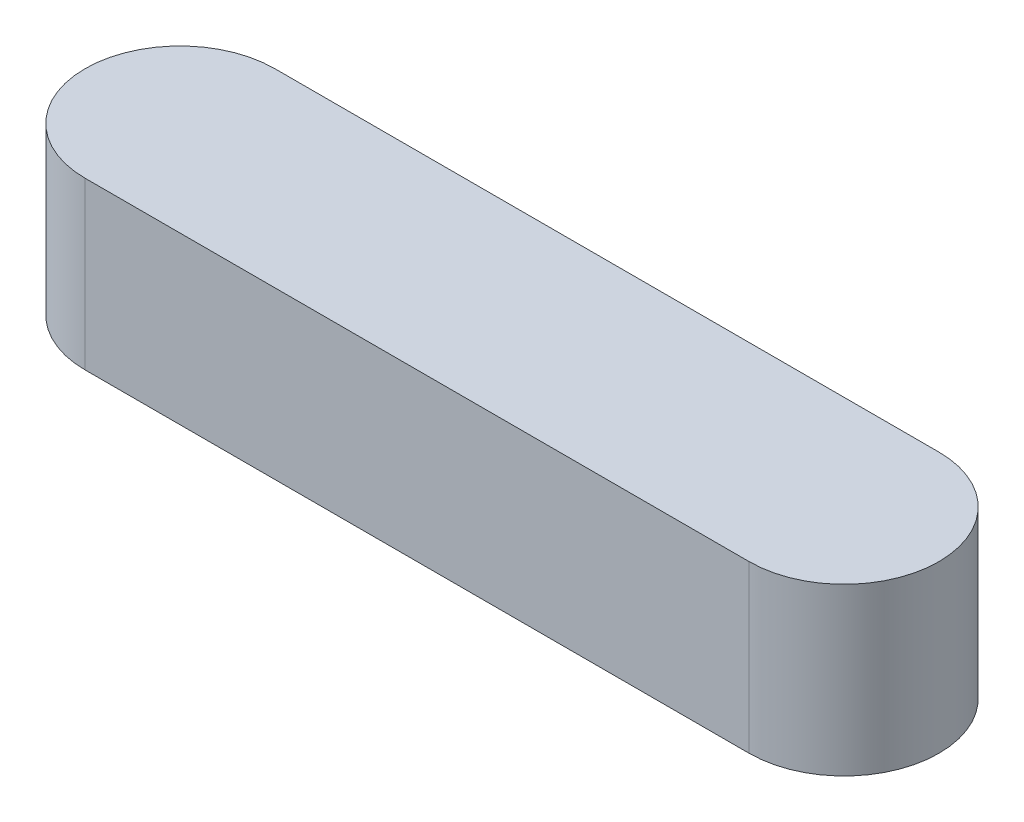
SolidWorks part; units mm, degrees
ref_plane "Спереди" through (0, 0, 0) normal (0, 0, 1) x (1, 0, 0)
ref_plane "Сверху" through (0, 0, 0) normal (0, 1, 0) x (1, 0, 0)
ref_plane "Справа" through (0, 0, 0) normal (1, 0, 0) x (0, 0, -1)
sketch "Эскиз1" plane through (0, 0, 0) normal (0, 1, 0) x (1, 0, 0)
  line L0 (0, 0) -> (28, 0) construction
  line L2 (0, 4) -> (28, 4)
  line L3 (0, -4) -> (28, -4)
  arc A0 (0, 4) -> (0, -4) centre (0, 0) ccw
  arc A1 (28, -4) -> (28, 4) centre (28, 0) ccw
  point P5 (14, 0)
extrude "Бобышка-Вытянуть1" add sketch "Эскиз1" along normal blind 7
